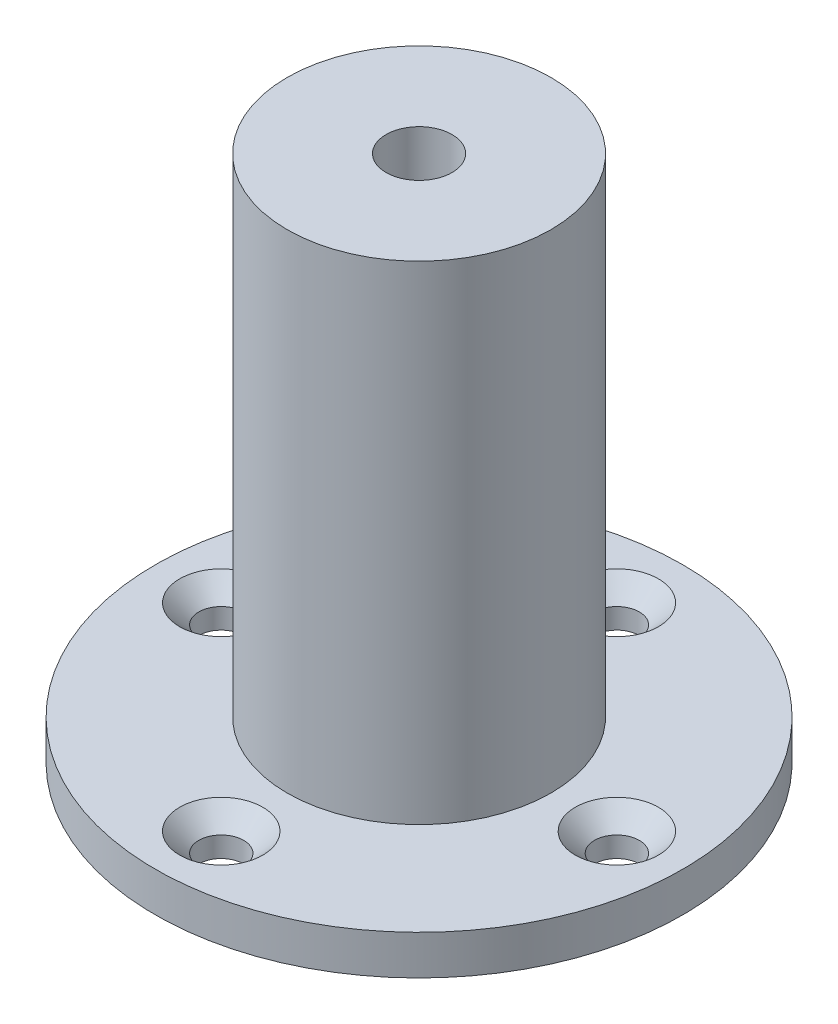
SolidWorks part; units mm, degrees
ref_plane "Front Plane" through (0, 0, 0) normal (0, 0, 1) x (1, 0, 0)
ref_plane "Top Plane" through (0, 0, 0) normal (0, 1, 0) x (1, 0, 0)
ref_plane "Right Plane" through (0, 0, 0) normal (1, 0, 0) x (0, 0, -1)
sketch "Sketch1" plane through (0, 0, 0) normal (0, 1, 0) x (1, 0, 0)
  circle A0 centre (0, 0) radius 10
  dimension "D1" = 20
extrude "Boss-Extrude1" add sketch "Sketch1" along normal blind 40 contours A0
sketch "Sketch2" plane through (0, 0, 0) normal (0, -1, 0) x (1, 0, 0)
  circle A0 centre (0, 0) radius 20
  dimension "D1" = 40
extrude "Boss-Extrude2" add sketch "Sketch2" against normal blind 3
hole_wizard "CSK for M3 Countersunk Flat Head Screw1" positions "Sketch4" profile "Sketch3" countersink size "M3" standard "ISO" end condition through all
sketch "Sketch4" plane through (0, 3, 0) normal (0, 1, 0) x (1, 0, 0)
  point P0 (0, 15)
  dimension "D1" = 15
sketch "Sketch3" plane through (0, 3, -15) normal (1, 0, 0) x (0, 0, 1)
  line L0 (0, 0) -> (0, 3)
  line L1 (0, 3) -> (1.7, 3)
  line L2 (1.7, 3) -> (1.7, 1.45)
  line L3 (1.7, 1.45) -> (3.15, 0)
  line L5 (3.15, 0) -> (0, 0)
  line L6 (-1.7, 1.45) -> (-3.15, 0) construction
  line L11 (0, -6.35) -> (0, 107.95) construction
  dimension "Thru Hole Dia." = 3.4
  dimension "Thru Hole Depth" = 3
  dimension "Near C'Sink Dia." = 6.3
  dimension "Near C'Sink Angle" = 90
pattern_circular "CirPattern1" count 4 over 360 about axis through (0, 0, 0) along (0, 1, 0) of "CSK for M3 Countersunk Flat Head Screw1"
hole_wizard "M6 Tapped Hole1" positions "Sketch6" profile "Sketch5" tap size "M6" standard "ISO"
sketch "Sketch6" plane through (0, 40, 0) normal (0, 1, 0) x (1, 0, 0)
  point P0 (0, 0)
sketch "Sketch5" plane through (0, 40, 0) normal (1, 0, 0) x (0, 0, 1)
  line L0 (0, 0) -> (0, 18.5022)
  line L1 (0, 18.5022) -> (2.5, 17)
  line L2 (2.5, 17) -> (2.5, 0)
  line L5 (2.5, 0) -> (0, 0)
  line L10 (0, 18.5022) -> (-2.5, 17) construction
  line L11 (0, -6.35) -> (0, 107.95) construction
  dimension "Tap Drill Dia." = 5
  dimension "Tap Drill Depth" = 17
  dimension "Drill Angle" = 118
